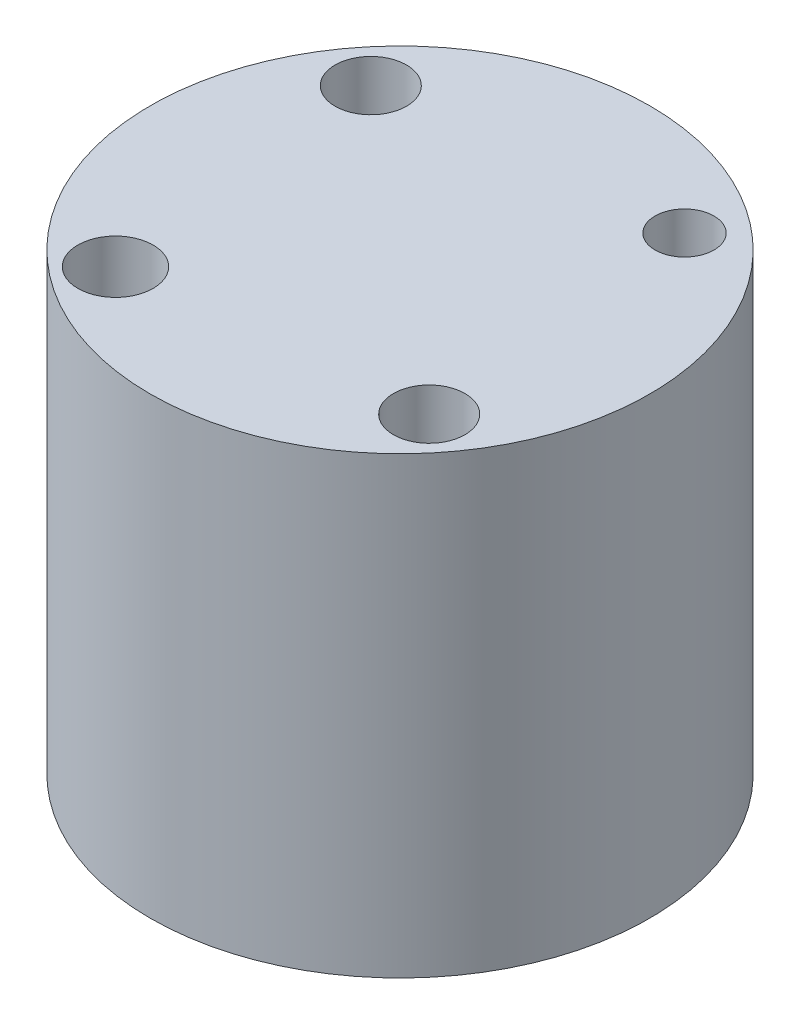
SolidWorks part; units mm, degrees
ref_plane "Front" through (0, 0, 0) normal (0, 0, 1) x (1, 0, 0)
ref_plane "Top" through (0, 0, 0) normal (0, 1, 0) x (1, 0, 0)
ref_plane "Right" through (0, 0, 0) normal (1, 0, 0) x (0, 0, -1)
sketch "Sketch1" plane through (0, 0, 0) normal (0, 1, 0) x (1, 0, 0)
  circle A0 centre (0, 0) radius 13.97
  circle A1 centre (-8.7751, 7.1413) radius 2
  circle A2 centre (7.1413, 8.7751) radius 1.65
  circle A3 centre (-7.1413, -8.7751) radius 2.105
  circle A4 centre (8.7751, -7.1413) radius 2
  dimension "D1" = 27.94
extrude "Boss-Extrude1" add sketch "Sketch1" along normal blind 25.4
